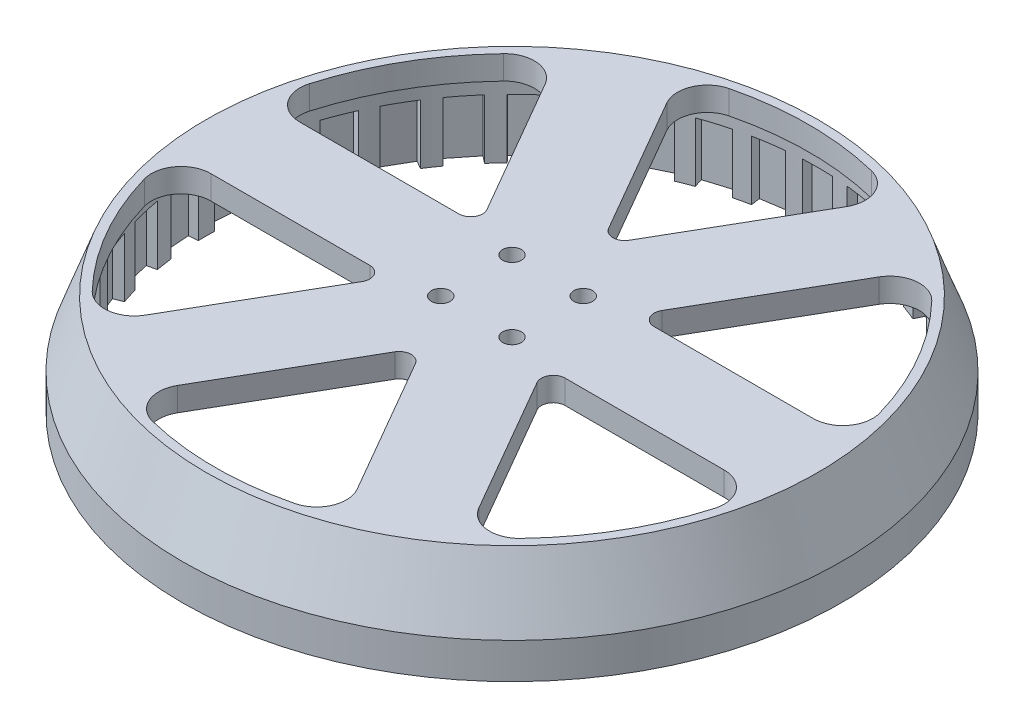
SolidWorks part; units mm, degrees
material "ABS"
ref_plane "Front Plane" through (0, 0, 0) normal (0, 0, 1) x (1, 0, 0)
ref_plane "Top Plane" through (0, 0, 0) normal (0, 1, 0) x (1, 0, 0)
ref_plane "Right Plane" through (0, 0, 0) normal (1, 0, 0) x (0, 0, -1)
sketch "Sketch1" plane through (0, 0, 0) normal (0, 0, 1) x (1, 0, 0)
  line L0 (0, 29) -> (0, 33)
  line L4 (51.5, 29) -> (51.5, 16)
  line L5 (51.5, 16) -> (55.5, 16)
  line L6 (55.5, 16) -> (55.5, 33)
  line L7 (55.5, 33) -> (0, 33)
  line L8 (0, 0) -> (0, 63.0003) construction
  line L11 (0, 29) -> (51.5, 29)
  dimension "D3" = 103
  dimension "D4" = 4
  dimension "D7" = 13
  dimension "D8" = 4
revolve "Main Revolve" add sketch "Sketch1" angle 360 about L8
sketch "Sketch2" plane through (0, 33, 0) normal (0, 1, 0) x (1, 0, 0)
  line L0 (0, 0) -> (0, 75.8468) construction
  line L1 (0, 0) -> (27.75, 48.0644) construction
  line L2 (15.1193, 41.1874) -> (1.7321, 18)
  line L3 (-15.1193, 41.1874) -> (-1.7321, 18)
  line L4 (0, 0) -> (-27.75, 48.0644) construction
  arc A0 (-11.988, 48.5416) -> (11.988, 48.5416) centre (0, 0) cw
  circle A2 centre (0, 0) radius 55.5 construction
  arc A3 (11.988, 48.5416) -> (15.1193, 41.1874) centre (10.7892, 43.6874) cw
  arc A6 (-11.988, 48.5416) -> (-15.1193, 41.1874) centre (-10.7892, 43.6874) ccw
  arc A7 (1.7321, 18) -> (-1.7321, 18) centre (0, 19) cw
  point P15 (0, 15)
  dimension "D5" = 50
  dimension "D6" = 2
  dimension "D7" = 5
  dimension "D3" = 5
  dimension "D1" = 30
  dimension "D2" = 30
  dimension "D4" = 15
extrude "Slot Cut" cut sketch "Sketch2" against normal through all
pattern_circular "Slot Cut Pattern" count 6 over 360 about axis through (0, 0, 0) along (0, 1, 0) of "Slot Cut"
sketch "Sketch4" plane through (0, 16, 0) normal (0, -1, 0) x (1, 0, 0)
  line L0 (-2.5, 53) -> (2.5, 53)
  line L1 (-2.5, 53) -> (-2.5, 51.4393)
  line L2 (2.5, 53) -> (2.5, 51.4393)
  circle A0 centre (0, 0) radius 51.5 construction
  arc A1 (2.5, 51.4393) -> (-2.5, 51.4393) centre (0, 0) ccw
  point P3 (0, 53)
  dimension "D2" = 1.5
  dimension "D1" = 5
extrude "Magnet Slots" cut sketch "Sketch4" against normal blind 10
pattern_circular "Magnet Cut Pattern" count 42 over 360 about axis through (0, 0, 0) along (0, 1, 0) of "Magnet Slots"
sketch "Sketch5" plane through (0, 33, 0) normal (0, 1, 0) x (1, 0, 0)
  line L1 (-6, -6) -> (6, -6) construction
  line L2 (-6, -6) -> (-6, 6) construction
  line L3 (-6, 6) -> (6, 6) construction
  line L4 (6, -6) -> (6, 6) construction
  line L5 (-6, -6) -> (6, 6) construction
  line L6 (-6, 6) -> (6, -6) construction
  circle A0 centre (-6, 6) radius 1.575
  circle A1 centre (-6, 6) radius 3
  circle A2 centre (6, 6) radius 3
  circle A3 centre (6, 6) radius 1.575
  circle A4 centre (6, -6) radius 3
  circle A5 centre (6, -6) radius 1.575
  circle A6 centre (-6, -6) radius 3
  circle A7 centre (-6, -6) radius 1.575
  point P0 (0, 0)
  point P11 (0, 0)
  point P15 (0, 0)
  point P19 (0, 0)
  point P23 (0, 0)
  dimension "D4" = 4
  dimension "D2" = 3.15
  dimension "D3" = 6
  dimension "D1" = 12
extrude "Cut-Extrude1" cut sketch "Sketch5" against normal blind 10 contours A0 | A3 | A5 | A7
chamfer "Chamfer1" distance 4 angle 70 1 edges at (0, 33, -55.5)
equation "\"D3@Sketch1\"=100+2*(1+0.5)"
equation "\"D2@Sketch5\"=3.15"
